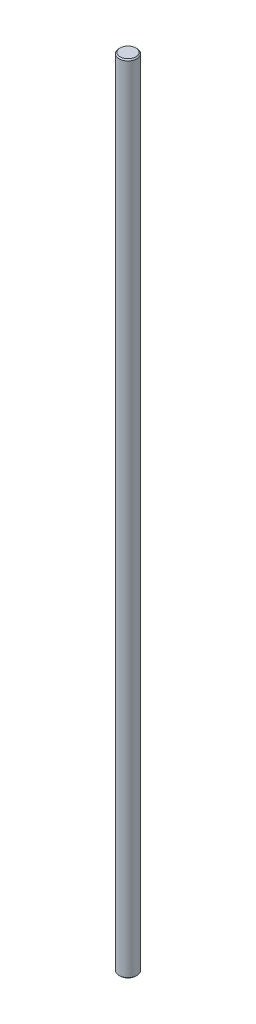
SolidWorks part; units mm, degrees
ref_plane "Front" through (0, 0, 0) normal (0, 0, 1) x (1, 0, 0)
ref_plane "Top" through (0, 0, 0) normal (0, 1, 0) x (1, 0, 0)
ref_plane "Right" through (0, 0, 0) normal (1, 0, 0) x (0, 0, -1)
sketch "Sketch1" plane through (0, 0, 0) normal (0, 1, 0) x (1, 0, 0)
  circle A0 centre (0, 0) radius 4
  dimension "D1" = 8
extrude "Boss-Extrude1" add sketch "Sketch1" along normal blind 357
chamfer "Chamfer1" distance 0.5 angle 45 2 edges at (0, 0, 4) (0, 357, 4)
